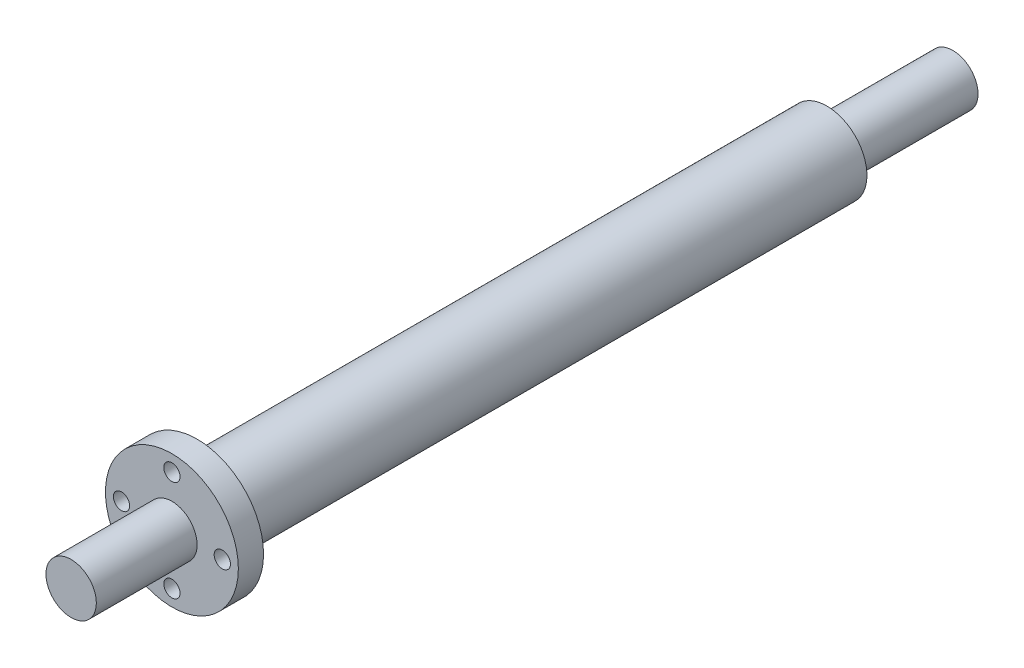
SolidWorks part; units mm, degrees
ref_plane "Płaszczyzna przednia" through (0, 0, 0) normal (0, 0, 1) x (1, 0, 0)
ref_plane "Płaszczyzna górna" through (0, 0, 0) normal (0, 1, 0) x (1, 0, 0)
ref_plane "Płaszczyzna prawa" through (0, 0, 0) normal (1, 0, 0) x (0, 0, -1)
sketch "Szkic1" plane through (0, 0, 0) normal (0, 0, 1) x (1, 0, 0)
  circle A0 centre (0, 0) radius 26.377
  circle A1 centre (0, 20) radius 3.2285
  circle A2 centre (20, 0) radius 3.2285
  circle A3 centre (0, -20) radius 3.2285
  circle A4 centre (-20, 0) radius 3.2285
  dimension "D1" = 20
  dimension "D2" = 4
extrude "Dodanie-wyciągnięcie1" add sketch "Szkic1" along normal blind 10
sketch "Szkic2" plane through (0, 0, 10) normal (0, 0, 1) x (1, 0, 0)
  circle A0 centre (0, 0) radius 10
extrude "Dodanie-wyciągnięcie2" add sketch "Szkic2" along normal blind 40
sketch "Szkic3" plane through (0, 0, 0) normal (0, 0, -1) x (-1, 0, 0)
  circle A0 centre (0, 0) radius 15.88
extrude "Dodanie-wyciągnięcie3" add sketch "Szkic3" along normal blind 300
sketch "Szkic4" plane through (0, 0, -300) normal (0, 0, -1) x (-1, 0, 0)
  circle A0 centre (0, 0) radius 15.88
  circle A1 centre (0, 0) radius 10
extrude "Wytnij-wyciągnięcie1" cut sketch "Szkic4" against normal blind 50
